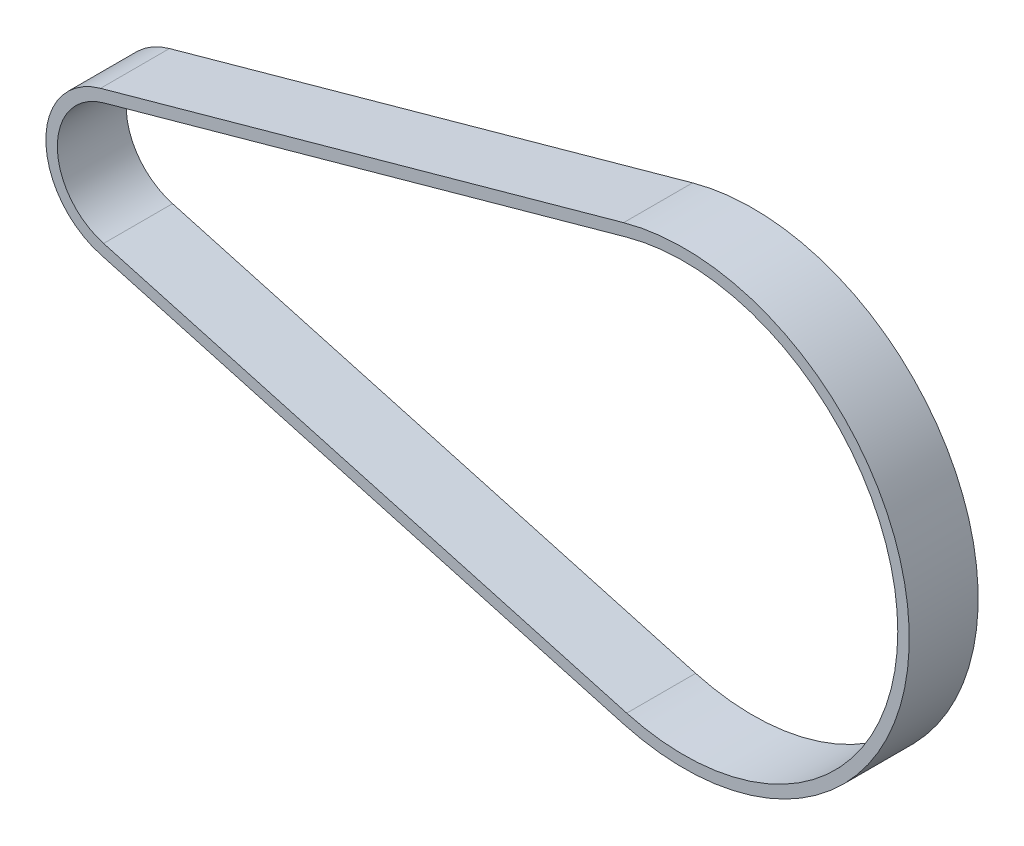
SolidWorks part; units mm, degrees
material "HYPALON"
ref_plane "Alzado" through (0, 0, 0) normal (0, 0, 1) x (1, 0, 0)
ref_plane "Planta" through (0, 0, 0) normal (0, 1, 0) x (1, 0, 0)
ref_plane "Vista lateral" through (0, 0, 0) normal (1, 0, 0) x (0, 0, -1)
sketch "Croquis1" plane through (0, 0, 0) normal (0, 0, 1) x (1, 0, 0)
  line L0 (-1.4712, 5.2996) -> (44.0695, 17.9415)
  line L1 (-1.4712, -5.2996) -> (44.0695, -17.9415)
  line L2 (-1.7386, 6.2632) -> (43.802, 18.9051)
  line L3 (-1.7386, -6.2632) -> (43.802, -18.9051)
  arc A0 (-1.4712, 5.2996) -> (-1.4712, -5.2996) centre (0, 0) ccw
  arc A1 (44.0695, -17.9415) -> (44.0695, 17.9415) centre (49.05, 0) ccw
  arc A2 (43.802, -18.9051) -> (43.802, 18.9051) centre (49.05, 0) ccw
  arc A3 (-1.7386, 6.2632) -> (-1.7386, -6.2632) centre (0, 0) ccw
  dimension "D1" = 11
  dimension "D2" = 37.24
  dimension "D3" = 49.05
  dimension "D4" = 1
extrude "Saliente-Extruir1" add sketch "Croquis1" along normal blind 6
